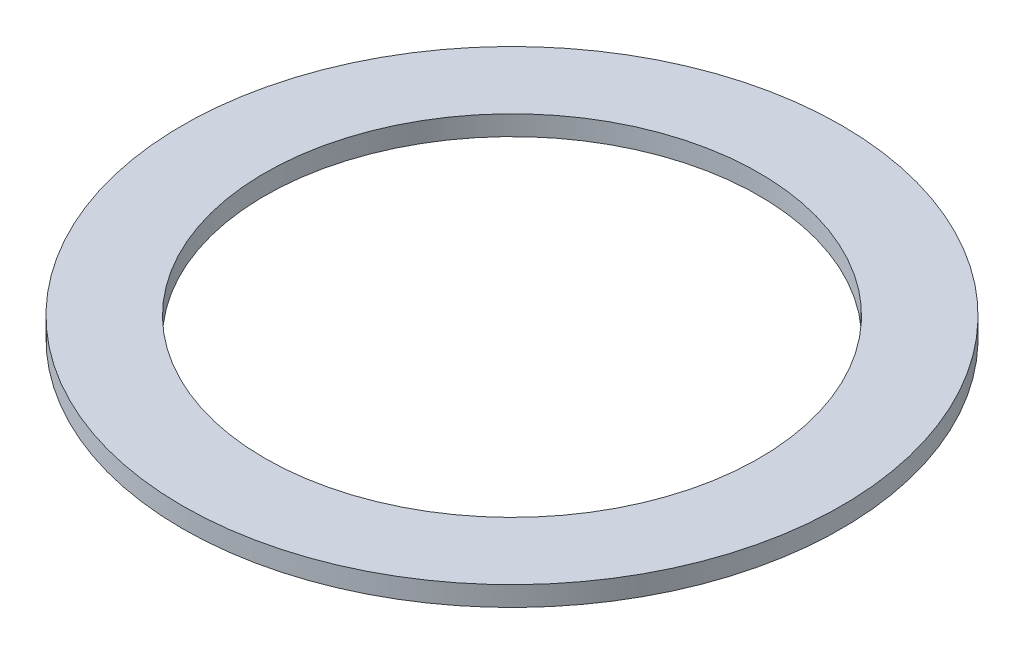
SolidWorks part; units mm, degrees
ref_plane "Front Plane" through (0, 0, 0) normal (0, 0, 1) x (1, 0, 0)
ref_plane "Top Plane" through (0, 0, 0) normal (0, 1, 0) x (1, 0, 0)
ref_plane "Right Plane" through (0, 0, 0) normal (1, 0, 0) x (0, 0, -1)
sketch "Sketch1" plane through (0, 0, 0) normal (1, 0, 0) x (0, 0, -1)
  line L0 (0, 14.2862) -> (0, -22.3775) construction
  line L1 (4.7625, 0) -> (0, 0) construction
  line L2 (4.7625, 0.1905) -> (6.35, 0.1905)
  line L3 (4.7625, 0.1905) -> (4.7625, -0.1905)
  line L4 (4.7625, -0.1905) -> (6.35, -0.1905)
  line L5 (6.35, 0.1905) -> (6.35, -0.1905)
  dimension "ID" = 9.525
  dimension "OD" = 12.7
  dimension "T" = 0.381
revolve "Revolve1" add sketch "Sketch1" angle 360 about L0
